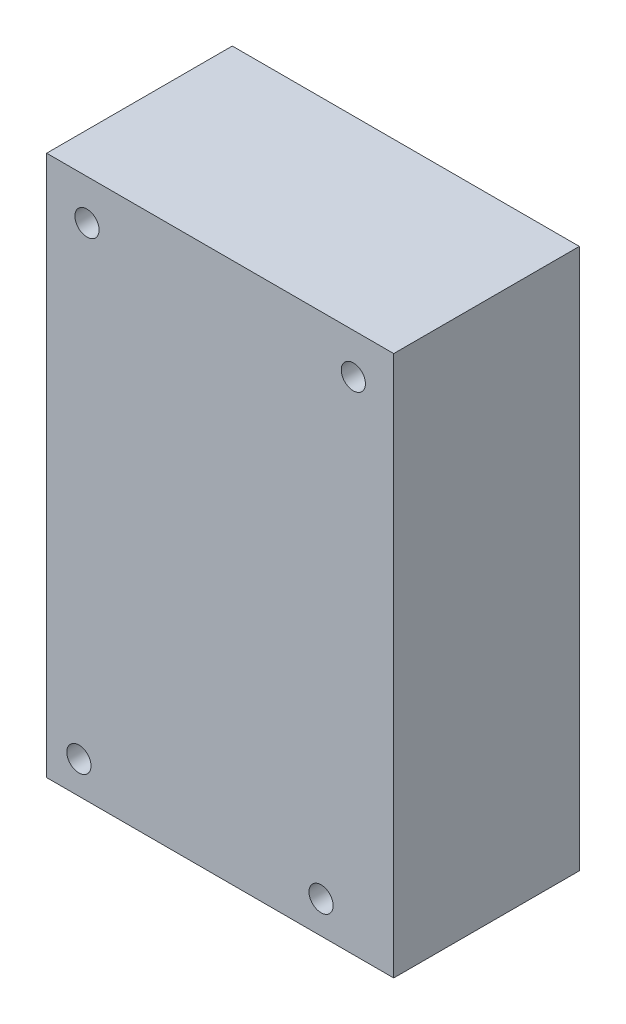
SolidWorks part; units mm, degrees
ref_plane "Front Plane" through (0, 0, 0) normal (1, 0, 0) x (0, 1, 0)
ref_plane "Top Plane" through (0, 0, 0) normal (0, 0, 1) x (0, 1, 0)
ref_plane "Right Plane" through (0, 0, 0) normal (0, 1, 0) x (-1, 0, 0)
sketch "Sketch1" plane through (0, 0, 0) normal (0, 0, 1) x (0, 1, 0)
  line L1 (-33.5, -21.5) -> (33.5, -21.5)
  line L2 (-33.5, -21.5) -> (-33.5, 21.5)
  line L3 (-33.5, 21.5) -> (33.5, 21.5)
  line L4 (33.5, -21.5) -> (33.5, 21.5)
  line L5 (-33.5, -21.5) -> (33.5, 21.5) construction
  line L6 (-33.5, 21.5) -> (33.5, -21.5) construction
  point P1 (0, 0)
  dimension "D1" = 67
  dimension "D2" = 43
extrude "Boss-Extrude1" add sketch "Sketch1" along normal blind 23
sketch "Sketch2" plane through (0, 0, 23) normal (0, 0, 1) x (1, 0, 0)
  line L0 (-16.5, 28.5) -> (16.5, 28.5) construction
  line L1 (-17.5, -29.5) -> (12.5, -29.5) construction
  line L2 (21.5, 33.5) -> (-21.5, 33.5) construction
  line L3 (-21.5, -33.5) -> (21.5, -33.5) construction
  line L4 (-21.5, 33.5) -> (-21.5, -33.5) construction
  circle A0 centre (-16.5, 28.5) radius 1.5
  circle A1 centre (16.5, 28.5) radius 1.5
  circle A2 centre (12.5, -29.5) radius 1.5
  circle A3 centre (-17.5, -29.5) radius 1.5
  dimension "D7" = 3
  dimension "D1" = 33
  dimension "D2" = 30
  dimension "D3" = 5
  dimension "D4" = 4
  dimension "D5" = 4
  dimension "D6" = 5
extrude "Cut-Extrude1" cut sketch "Sketch2" against normal up to next
